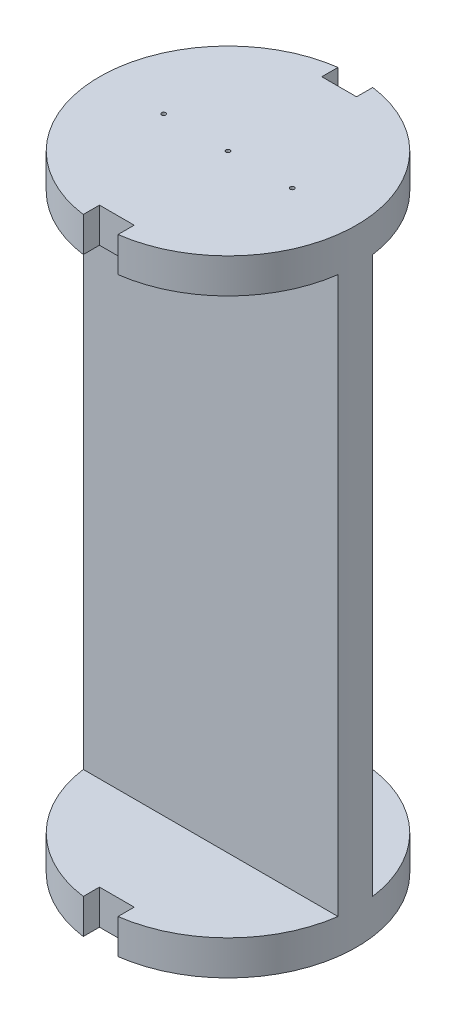
SolidWorks part; units mm, degrees
material "Balsa"
ref_plane "Front Plane" through (0, 0, 0) normal (0, 0, 1) x (1, 0, 0)
ref_plane "Top Plane" through (0, 0, 0) normal (0, 1, 0) x (1, 0, 0)
ref_plane "Right Plane" through (0, 0, 0) normal (1, 0, 0) x (0, 0, -1)
sketch "Sketch1" plane through (0, 0, 0) normal (0, 1, 0) x (1, 0, 0)
  circle A0 centre (0, 0) radius 37
  dimension "D1" = 74
extrude "Boss-Extrude1" add sketch "Sketch1" along normal blind 10
ref_plane "Plane1" through (0, 180, 0) normal (0, 1, 0) x (1, 0, 0)
sketch "Sketch2" plane through (0, 180, 0) normal (0, 1, 0) x (1, 0, 0)
  circle A0 centre (0, 0) radius 37 construction
  circle A1 centre (0, 0) radius 37
extrude "Boss-Extrude2" add sketch "Sketch2" against normal blind 10 separate body
sketch "Sketch3" plane through (0, 10, 0) normal (0, 1, 0) x (1, 0, 0)
  line L1 (36.6606, 5) -> (-36.6606, 5)
  line L3 (36.6606, -5) -> (-36.6606, -5)
  line L5 (36.6606, 5) -> (-36.6606, -5) construction
  line L6 (36.6606, -5) -> (-36.6606, 5) construction
  circle A0 centre (0, 0) radius 37 construction
  arc A1 (-36.6606, 5) -> (-36.6606, -5) centre (0, 0) ccw
  arc A2 (36.6606, -5) -> (36.6606, 5) centre (0, 0) ccw
  point P0 (0, 0)
  dimension "D1" = 10
extrude "Boss-Extrude3" add sketch "Sketch3" along normal up to next
sketch "Sketch4" plane through (0, 180, 0) normal (0, 1, 0) x (1, 0, 0)
  line L0 (0, 0) -> (7.5059, 0) construction
  line L1 (5, 42) -> (-5, 42)
  line L2 (5, 42) -> (5, 32)
  line L3 (5, 32) -> (-5, 32)
  line L4 (-5, 42) -> (-5, 32)
  line L5 (5, 42) -> (-5, 32) construction
  line L6 (5, 32) -> (-5, 42) construction
  line L7 (5, -32) -> (-5, -32)
  line L8 (-5, -42) -> (-5, -32)
  line L9 (5, -42) -> (-5, -42)
  line L10 (5, -42) -> (5, -32)
  circle A0 centre (0, 0) radius 37 construction
  point P0 (0, 37)
  dimension "D1" = 10
  dimension "D2" = 10
extrude "Cut-Extrude1" cut sketch "Sketch4" against normal through all
sketch "Sketch5" plane through (0, 180, 0) normal (0, 1, 0) x (1, 0, 0)
  line L0 (0, 0) -> (-37, 0) construction
  line L1 (36.6606, 5) -> (-36.6606, 5)
  line L3 (36.6606, -5) -> (-36.6606, -5)
  line L5 (36.6606, 5) -> (-36.6606, -5) construction
  line L6 (36.6606, -5) -> (-36.6606, 5) construction
  line L7 (0, 0) -> (37, 0) construction
  arc A0 (-5, 36.6606) -> (-5, -36.6606) centre (0, 0) ccw construction
  arc A1 (-5, 36.6606) -> (-5, -36.6606) centre (0, 0) ccw
  arc A2 (-36.6606, -5) -> (-5, -36.6606) centre (0, 0) ccw
  arc A3 (5, -36.6606) -> (5, 36.6606) centre (0, 0) ccw construction
  arc A4 (36.6606, -5) -> (36.6606, 5) centre (0, 0) ccw
  circle A5 centre (-18.5, 0) radius 0.6
  circle A6 centre (0, 0) radius 0.6
  circle A9 centre (18.5, 0) radius 0.6
  point P0 (0, 0)
  dimension "D2" = 1.2
  dimension "D1" = 10
extrude "Cut-Extrude2" cut sketch "Sketch5" against normal blind 19.75 contours A5 | A6 | A9
sketch "Sketch7" plane through (0, 0, 0) normal (0, -1, 0) x (1, 0, 0)
  line L0 (0, 0) -> (-38.5, 0) construction
  line L5 (38.1739, 5) -> (-36.6866, -4.8052) construction
  line L6 (38.1739, -5) -> (-38.1739, 5) construction
  line L7 (0, 0) -> (38.5, 0) construction
  circle A0 centre (0, 0) radius 37 construction
  circle A3 centre (-19.25, 0) radius 0.6
  circle A4 centre (0, 0) radius 0.6
  circle A5 centre (19.25, 0) radius 0.6
  point P0 (0, 0)
  dimension "D2" = 1.2
extrude "Cut-Extrude4" cut sketch "Sketch7" against normal blind 19.75
equation "\"diamfuselaje int\"=74"
equation "\"D1@Sketch1\"=\"diamfuselaje int\""
